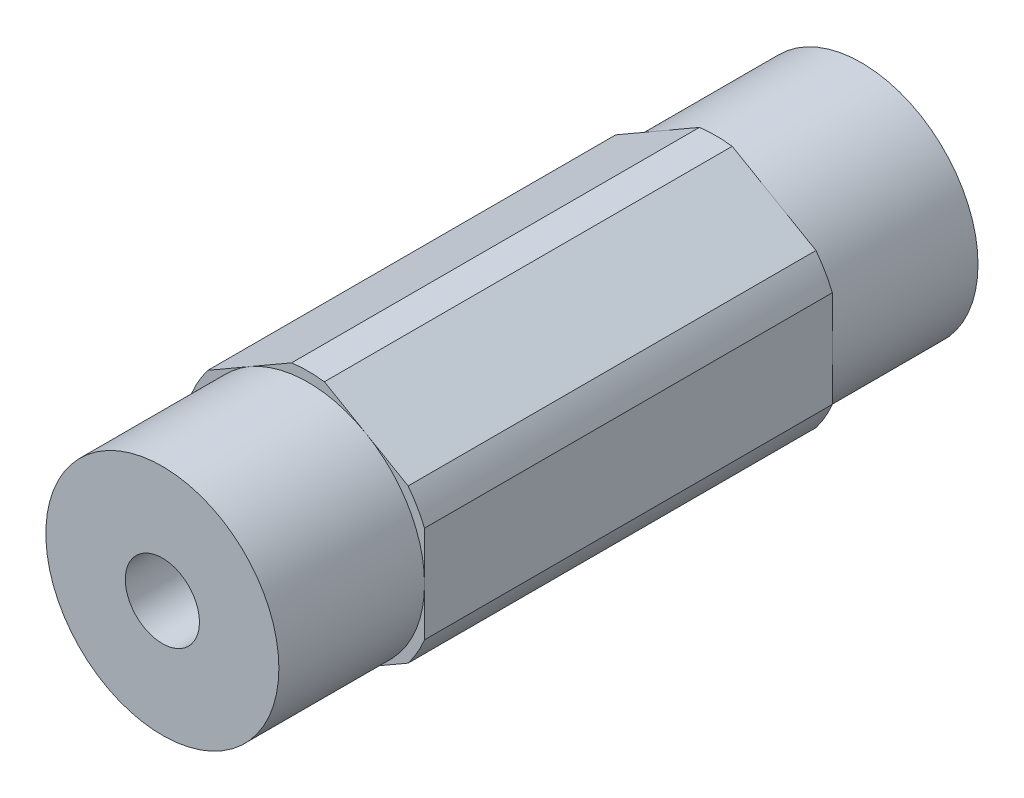
SolidWorks part; units mm, degrees
material "7075-T6 (SN)"
ref_plane "Front Plane" through (0, 0, 0) normal (0, 0, 1) x (1, 0, 0)
ref_plane "Top Plane" through (0, 0, 0) normal (0, 1, 0) x (1, 0, 0)
ref_plane "Right Plane" through (0, 0, 0) normal (1, 0, 0) x (0, 0, -1)
sketch "Sketch1" plane through (0, 0, 0) normal (0, 0, 1) x (1, 0, 0)
  line L1 (0, 7.3323) -> (-6.35, 3.6662)
  line L2 (-6.35, 3.6662) -> (-6.35, -3.6662)
  line L3 (-6.35, -3.6662) -> (0, -7.3323)
  line L4 (0, -7.3323) -> (6.35, -3.6662)
  line L5 (6.35, -3.6662) -> (6.35, 3.6662)
  line L6 (6.35, 3.6662) -> (0, 7.3323)
  circle A0 centre (0, 0) radius 6.35 construction
  circle A1 centre (0, 0) radius 6.875
  circle A2 centre (0, 0) radius 2.0193
  dimension "D1" = 12.7
  dimension "D2" = 4.0386
  dimension "D3" = 13.75
extrude "Boss-Extrude1" add sketch "Sketch1" along normal mid plane 38.1 contours L5 A1 L6 L1 L2 L3 L4 A2
hole_wizard "#10-32 Tapped Hole1" positions "3DSketch2" profile "Sketch3" tap size "#10-32" standard "ANSI Inch"
sketch3d "3DSketch2"
  circle A0 centre (0, 0, -19.05) radius 2.0193 construction
  circle A1 centre (0, 0, 19.05) radius 2.0193 construction
  point P0 (0, 0, 19.05)
  point P2 (0, 0, -19.05)
  point P7 (0, 0, -17.0307)
  point P10 (0, 0, 21.0693)
sketch "Sketch3" plane through (0, 0, 19.05) normal (1, 0, 0) x (0, -1, 0)
  line L0 (0, 0) -> (0, 13.2428)
  line L1 (0, 13.2428) -> (2.0193, 12.0294)
  line L2 (2.0193, 12.0294) -> (2.0193, 0)
  line L5 (2.0193, 0) -> (0, 0)
  line L10 (0, 13.2428) -> (-2.0193, 12.0294) construction
  line L11 (0, -6.35) -> (0, 107.95) construction
  dimension "Tap Drill Dia." = 4.0386
  dimension "Tap Drill Depth" = 12.0294
  dimension "Drill Angle" = 118
cosmetic thread "Hole Thread1" parameters "D1"=9.652, "D2"=4.826
cosmetic thread "Hole Thread2" parameters "D1"=9.652, "D2"=4.826
sketch "Sketch5" plane through (0, 0, 19.05) normal (0, 0, 1) x (1, 0, 0)
  circle A0 centre (0, 0) radius 6.875
  circle A1 centre (0, 0) radius 6.35
  arc A2 (0.893, 6.8168) -> (-0.893, 6.8168) centre (0, 0) ccw construction
  dimension "D1" = 12.7
extrude "Cut-Extrude1" cut sketch "Sketch5" against normal blind 7.9375
mirror "Mirror1" about plane through (0, 0, 0) normal (0, 0, 1) of "Cut-Extrude1"
equation "\"D3@Sketch1\"=13.75mm"
